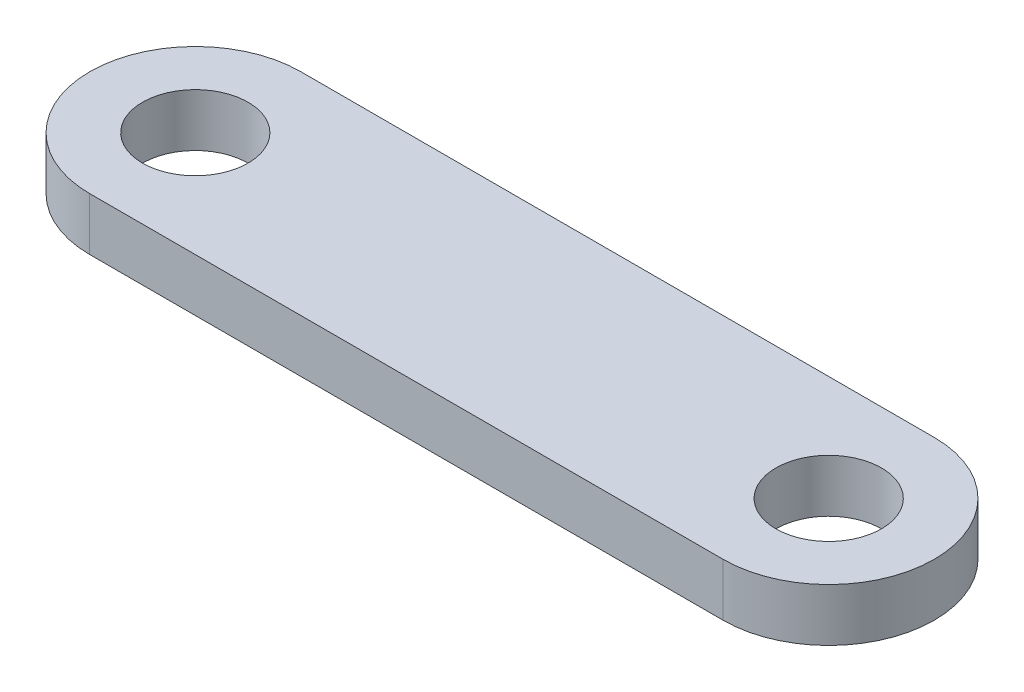
SolidWorks part; units mm, degrees
ref_plane "Front Plane" through (0, 0, 0) normal (0, 0, 1) x (1, 0, 0)
ref_plane "Top Plane" through (0, 0, 0) normal (0, 1, 0) x (1, 0, 0)
ref_plane "Right Plane" through (0, 0, 0) normal (1, 0, 0) x (0, 0, -1)
sketch "Sketch1" plane through (0, 0, 0) normal (0, 1, 0) x (1, 0, 0)
  line L0 (-51.223, 6.9065) -> (8.777, 6.9065) construction
  line L1 (-51.223, 16.9065) -> (8.777, 16.9065)
  line L2 (-51.223, -3.0935) -> (8.777, -3.0935)
  arc A0 (-51.223, 16.9065) -> (-51.223, -3.0935) centre (-51.223, 6.9065) ccw
  arc A1 (8.777, -3.0935) -> (8.777, 16.9065) centre (8.777, 6.9065) ccw
  circle A2 centre (-51.223, 6.9065) radius 5
  circle A3 centre (8.777, 6.9065) radius 5
  point P2 (-21.223, 6.9065)
  dimension "D3" = 10
  dimension "D4" = 10
  dimension "D1" = 60
  dimension "D2" = 20
extrude "Boss-Extrude1" add sketch "Sketch1" along normal blind 5
